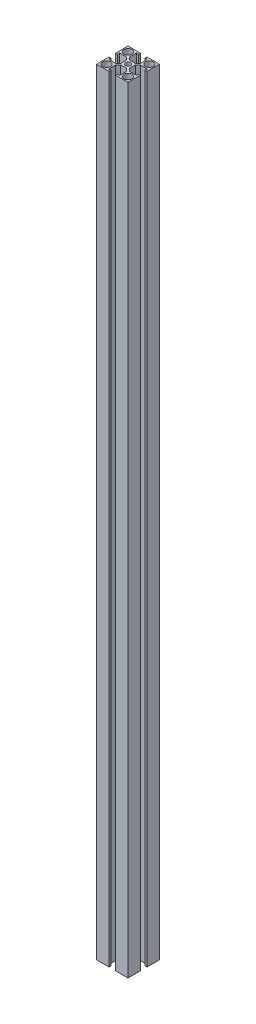
SolidWorks part; units mm, degrees
material "6061 合金"
ref_plane "前视基准面" through (0, 0, 0) normal (0, 0, 1) x (1, 0, 0)
ref_plane "上视基准面" through (0, 0, 0) normal (0, 1, 0) x (1, 0, 0)
ref_plane "右视基准面" through (0, 0, 0) normal (1, 0, 0) x (0, 0, -1)
other "Configuration Table"
sketch "草图2" plane through (0, 0, 0) normal (0, 1, 0) x (1, 0, 0)
  line L0 (-3.15, 15) -> (-3.15, 13.2)
  line L5 (15, -15) -> (-15, -15)
  line L6 (15, -15) -> (15, 15)
  line L7 (15, 15) -> (-15, 15)
  line L8 (-15, -15) -> (-15, 15)
  line L9 (15, -15) -> (-15, 15) construction
  line L10 (15, 15) -> (-15, -15) construction
  line L11 (4.1, -4.1) -> (-4.1, -4.1)
  line L12 (4.1, -4.1) -> (4.1, 4.1)
  line L13 (4.1, 4.1) -> (-4.1, 4.1)
  line L14 (-4.1, -4.1) -> (-4.1, 4.1)
  line L15 (4.1, -4.1) -> (-4.1, 4.1) construction
  line L16 (4.1, 4.1) -> (-4.1, -4.1) construction
  line L17 (-3.15, 13.2) -> (-5.25, 13.2)
  line L22 (-5.25, 13.2) -> (-5.25, 6.5228)
  line L23 (-5.25, 6.5228) -> (-2.8272, 4.1)
  line L24 (0, 500) -> (0, -500) construction
  line L25 (-500, 0) -> (500, 0) construction
  line L26 (5.25, 6.5228) -> (2.8272, 4.1)
  line L27 (5.25, 13.2) -> (5.25, 6.5228)
  line L28 (3.15, 13.2) -> (5.25, 13.2)
  line L29 (3.15, 15) -> (3.15, 13.2)
  line L30 (15, 3.15) -> (13.2, 3.15)
  line L31 (13.2, 3.15) -> (13.2, 5.25)
  line L32 (13.2, 5.25) -> (6.5228, 5.25)
  line L33 (6.5228, 5.25) -> (4.1, 2.8272)
  line L34 (6.5228, -5.25) -> (4.1, -2.8272)
  line L35 (13.2, -5.25) -> (6.5228, -5.25)
  line L36 (13.2, -3.15) -> (13.2, -5.25)
  line L37 (15, -3.15) -> (13.2, -3.15)
  line L38 (3.15, -15) -> (3.15, -13.2)
  line L39 (3.15, -13.2) -> (5.25, -13.2)
  line L40 (5.25, -13.2) -> (5.25, -6.5228)
  line L41 (5.25, -6.5228) -> (2.8272, -4.1)
  line L42 (-5.25, -6.5228) -> (-2.8272, -4.1)
  line L43 (-5.25, -13.2) -> (-5.25, -6.5228)
  line L44 (-3.15, -13.2) -> (-5.25, -13.2)
  line L45 (-3.15, -15) -> (-3.15, -13.2)
  line L46 (-15, -3.15) -> (-13.2, -3.15)
  line L47 (-13.2, -3.15) -> (-13.2, -5.25)
  line L48 (-13.2, -5.25) -> (-6.5228, -5.25)
  line L49 (-6.5228, -5.25) -> (-4.1, -2.8272)
  line L50 (-6.5228, 5.25) -> (-4.1, 2.8272)
  line L51 (-13.2, 5.25) -> (-6.5228, 5.25)
  line L52 (-13.2, 3.15) -> (-13.2, 5.25)
  line L53 (-15, 3.15) -> (-13.2, 3.15)
  circle A5 centre (0, 0) radius 2.4
  circle A6 centre (10.2239, 10.2239) radius 3.8
  circle A7 centre (10.2239, -10.2239) radius 3.8
  circle A8 centre (-10.2239, -10.2239) radius 3.8
  circle A9 centre (-10.2239, 10.2239) radius 3.8
  point P65 (0, 0)
  dimension "D2" = 4.8
  dimension "D8" = 0.9
  dimension "D3" = 7.6
  dimension "D1" = 30
  dimension "D4" = 1.8
  dimension "D5" = 6.3
  dimension "D6" = 8.2
  dimension "D7" = 10.5
  dimension "D9" = 4
extrude "凸台-拉伸1" add sketch "草图2" along normal blind 740 contours L49 L48 L47 L46 L8 L5 L45 L44 L43 L42 L11 L14 A8 | L14 L11 L12 L13 A5 | L41 L40 L39 L38 L5 L6 L37 L36 L35 L34 L12 L11 A7 | L33 L32 L31 L30 L6 L7 L29 L28 L27 L26 L13 L12 A6 | L8 L53 L52 L51 L50 L14 L13 L23 L22 L17 L0 L7 A9
sketch "草图3" [suppressed] plane through (0, 0, -15) normal (0, 0, -1) x (-1, 0, 0)
  line L0 (-15, 280.5) -> (15, 280.5) construction
  line L1 (-15, 561) -> (-15, 0) construction
  line L2 (15, 561) -> (15, 0) construction
  circle A0 centre (0, 280.5) radius 4.5461
sketch "草图4" [suppressed] plane through (15, 0, 0) normal (1, 0, 0) x (0, 0, -1)
  line L0 (-2.8272, 462) -> (2.8272, 462) construction
  line L1 (15, 231) -> (-15, 231) construction
  line L2 (15, 462) -> (15, 0) construction
  line L3 (-15, 462) -> (-15, 0) construction
  circle A2 centre (0, 402) radius 4.25
  circle A3 centre (0, 60) radius 4.25
  point P4 (0, 462)
  dimension "D1" = 8.5
  dimension "D3" = 60
  dimension "D2" = 60
extrude "切除-拉伸1" [suppressed] cut sketch "草图4" against normal through all both and the other way through all
sketch "草图5" [suppressed] plane through (0, 0, 15) normal (0, 0, 1) x (1, 0, 0)
  line L0 (-15, 231) -> (15, 231) construction
  line L1 (-15, 462) -> (-15, 0) construction
  line L2 (15, 462) -> (15, 0) construction
  circle A0 centre (0, 366) radius 3
  circle A1 centre (0, 231) radius 3
  circle A2 centre (0, 96) radius 3
  dimension "D1" = 6
  dimension "D2" = 135
extrude "切除-拉伸2" [suppressed] cut sketch "草图5" against normal through all both and the other way through all
sketch "草图6" [suppressed] plane through (0, 0, 15) normal (0, 0, 1) x (1, 0, 0)
  circle A0 centre (0, 366) radius 4
  circle A1 centre (0, 231) radius 4
  circle A2 centre (0, 96) radius 4
  dimension "D1" = 19.5976
extrude "切除-拉伸3" [suppressed] cut sketch "草图6" against normal up to surface and the other way through all
sketch "草图7" [suppressed] plane through (0, 0, -15) normal (0, 0, -1) x (-1, 0, 0)
  line L0 (-15, 280.5) -> (15, 280.5) construction
  line L1 (-15, 561) -> (-15, 0) construction
  line L2 (15, 561) -> (15, 0) construction
  line L4 (-2.8272, 0) -> (2.8272, 0) construction
  circle A0 centre (0, 80.5) radius 3
  circle A1 centre (0, 280.5) radius 3
  circle A2 centre (0, 480.5) radius 3
  point P10 (0, 0)
  dimension "D2" = 6
  dimension "D3" = 200
  dimension "D1" = 80.5
extrude "切除-拉伸4" [suppressed] cut sketch "草图7" against normal through all both and the other way through all
sketch "草图8" [suppressed] plane through (0, 0, -15) normal (0, 0, -1) x (-1, 0, 0)
  circle A0 centre (0, 80.5) radius 7
  circle A1 centre (0, 280.5) radius 7
  circle A2 centre (0, 480.5) radius 7
  dimension "D1" = 14
extrude "切除-拉伸5" [suppressed] cut sketch "草图8" against normal up to surface and the other way through all
sketch "草图9" [suppressed] plane through (0, 0, -15) normal (0, 0, -1) x (-1, 0, 0)
  circle A0 centre (0, 96) radius 7
  circle A1 centre (0, 231) radius 7
  circle A2 centre (0, 366) radius 7
  dimension "D1" = 14
extrude "切除-拉伸6" [suppressed] cut sketch "草图9" against normal up to surface (10.9 mm away)
sketch "草图10" [suppressed] plane through (-15, 0, 0) normal (-1, 0, 0) x (0, 0, 1)
  line L0 (15, 561) -> (3.15, 561) construction
  line L1 (15, 0) -> (3.15, 0) construction
  circle A0 centre (0, 501) radius 4.25
  circle A1 centre (0, 60) radius 4.25
  dimension "D2" = 60
  dimension "D3" = 8.5
  dimension "D1" = 60
extrude "切除-拉伸7" [suppressed] cut sketch "草图10" against normal through all
